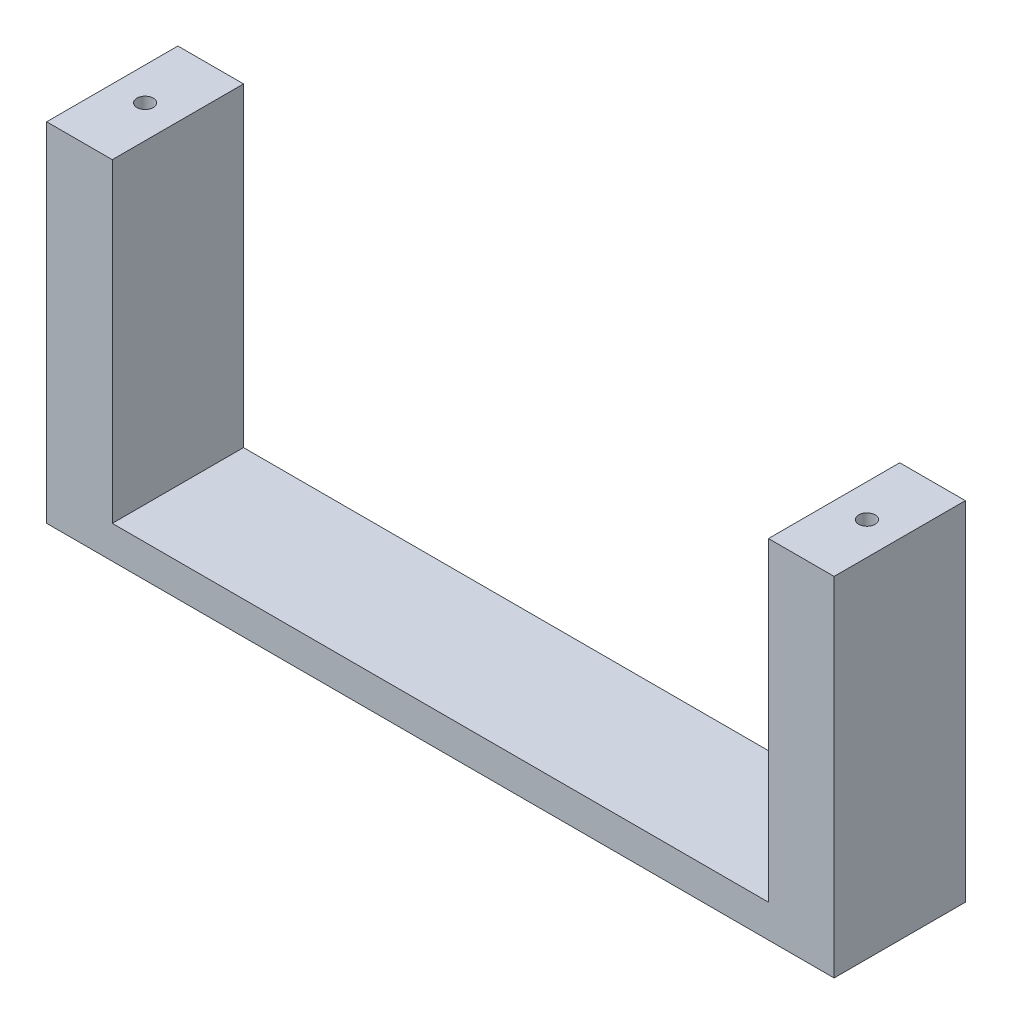
SolidWorks part; units mm, degrees
ref_plane "Alzado" through (0, 0, 0) normal (0, 0, 1) x (1, 0, 0)
ref_plane "Planta" through (0, 0, 0) normal (0, 1, 0) x (1, 0, 0)
ref_plane "Vista lateral" through (0, 0, 0) normal (1, 0, 0) x (0, 0, -1)
sketch "Croquis1" plane through (0, 0, 0) normal (0, 1, 0) x (1, 0, 0)
  line L1 (60, -10) -> (-60, -10)
  line L2 (60, -10) -> (60, 10)
  line L3 (60, 10) -> (-60, 10)
  line L4 (-60, -10) -> (-60, 10)
  line L5 (60, -10) -> (-60, 10) construction
  line L6 (60, 10) -> (-60, -10) construction
  point P0 (0, 0)
  dimension "D1" = 20
  dimension "D2" = 120
extrude "Saliente-Extruir1" add sketch "Croquis1" along normal blind 5
sketch "Croquis2" plane through (0, 5, 0) normal (0, 1, 0) x (1, 0, 0)
  line L0 (-60, -10) -> (60, -10) construction
  line L1 (60, 10) -> (50, 10)
  line L2 (60, 10) -> (60, -10)
  line L3 (60, -10) -> (50, -10)
  line L4 (50, 10) -> (50, -10)
  line L6 (-60, 10) -> (-50, 10)
  line L7 (-60, 10) -> (-60, -10)
  line L8 (-60, -10) -> (-50, -10)
  line L9 (-50, 10) -> (-50, -10)
  dimension "D1" = 10
  dimension "D2" = 10
extrude "Saliente-Extruir2" add sketch "Croquis2" along normal blind 48
sketch "Croquis3" plane through (0, 53, 0) normal (0, 1, 0) x (1, 0, 0)
  line L0 (55, 10) -> (55, -10) construction
  line L1 (60, 10) -> (50, 10) construction
  line L2 (50, -10) -> (60, -10) construction
  line L3 (60, 0) -> (-60, 0) construction
  line L4 (60, -10) -> (60, 10) construction
  line L5 (-60, 10) -> (-60, -10) construction
  line L6 (-55, 10) -> (-55, -10) construction
  line L7 (-50, 10) -> (-60, 10) construction
  line L8 (-60, -10) -> (-50, -10) construction
  circle A0 centre (-55, 0) radius 1.25
  circle A1 centre (55, 0) radius 1.25
  point P18 (-55, 0)
  point P19 (55, 0)
  dimension "D1" = 2.5
  dimension "D2" = 2.5
extrude "Cortar-Extruir1" cut sketch "Croquis3" against normal blind 10
